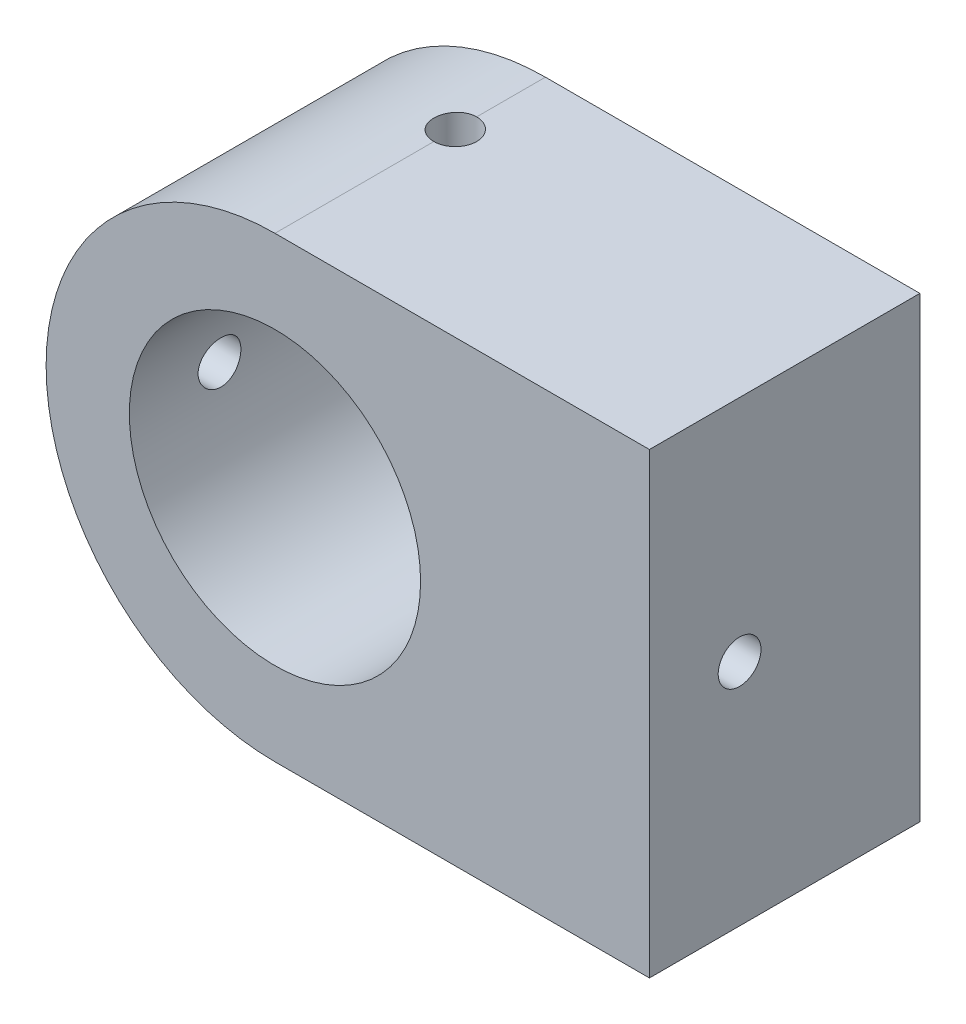
SolidWorks part; units mm, degrees
ref_plane "Front Plane" through (0, 0, 0) normal (1, 0, 0) x (0, 1, 0)
ref_plane "Top Plane" through (0, 0, 0) normal (0, 0, 1) x (0, 1, 0)
ref_plane "Right Plane" through (0, 0, 0) normal (0, 1, 0) x (-1, 0, 0)
sketch "Sketch1" plane through (0, 0, 0) normal (0, 0, 1) x (0, 1, 0)
  line L0 (-34.925, 0) -> (-34.925, -57.15)
  line L1 (-34.925, -57.15) -> (34.925, -57.15)
  line L2 (34.925, -57.15) -> (34.925, 0)
  circle A0 centre (0, 0) radius 22.225
  circle A1 centre (0, 0) radius 34.925 construction
  arc A2 (-34.925, 0) -> (34.925, 0) centre (0, 0) cw
  dimension "D1" = 44.45
  dimension "D2" = 12.7
  dimension "D3" = 34.925
extrude "Boss-Extrude1" add sketch "Sketch1" along normal blind 41.275
sketch "Sketch2" plane through (0, 0, 0) normal (1, 0, 0) x (0, 1, 0)
  line L0 (0, 0) -> (0, 13.7583) construction
  line L1 (-34.925, 0) -> (34.925, 0) construction
  line L2 (0, 13.7583) -> (0, 27.5167) construction
  line L3 (0, 27.5167) -> (0, 41.275) construction
  line L4 (-34.925, 41.275) -> (34.925, 41.275) construction
  circle A0 centre (0, 27.5167) radius 3.2639
  point P0 (0, 13.7583)
  point P1 (0, 27.5167)
  dimension "D1" = 6.5278
extrude "Cut-Extrude1" cut sketch "Sketch2" against normal through all both and the other way through all
sketch "Sketch3" plane through (0, 0, 0) normal (0, 1, 0) x (-1, 0, 0)
  circle A0 centre (0, 13.7583) radius 3.2639
  point P0 (0, 13.7583)
  dimension "D1" = 6.5278
extrude "Cut-Extrude2" cut sketch "Sketch3" against normal through all both and the other way through all
